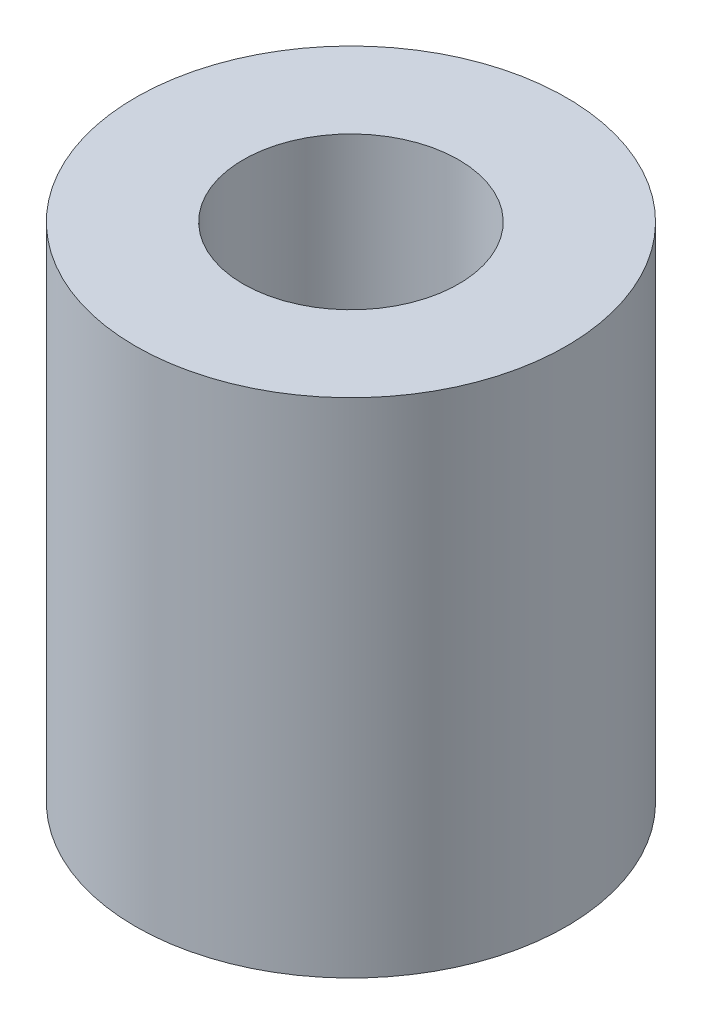
SolidWorks part; units mm, degrees
ref_plane "前视基准面" through (0, 0, 0) normal (0, 0, 1) x (1, 0, 0)
ref_plane "上视基准面" through (0, 0, 0) normal (0, 1, 0) x (1, 0, 0)
ref_plane "右视基准面" through (0, 0, 0) normal (1, 0, 0) x (0, 0, -1)
sketch "草图1" plane through (0, 0, 0) normal (0, 1, 0) x (1, 0, 0)
  circle A0 centre (0, 0) radius 1.5
  circle A1 centre (0, 0) radius 3
  dimension "D1" = 3
  dimension "D2" = 6
extrude "凸台-拉伸1" add sketch "草图1" along normal blind 7
